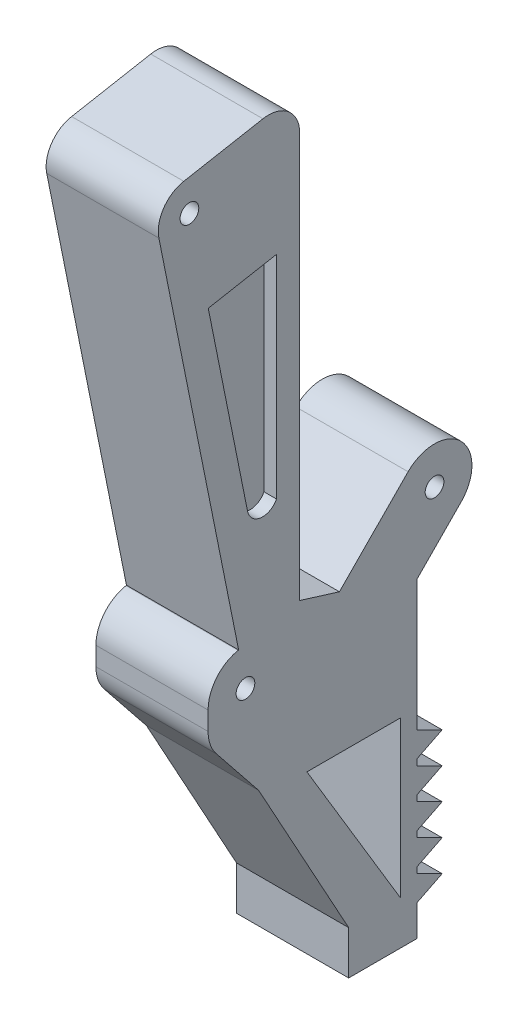
SolidWorks part; units mm, degrees
ref_plane "Front Plane" through (0, 0, 0) normal (0, 0, 1) x (1, 0, 0)
ref_plane "Top Plane" through (0, 0, 0) normal (0, 1, 0) x (1, 0, 0)
ref_plane "Right Plane" through (0, 0, 0) normal (1, 0, 0) x (0, 0, -1)
sketch "Sketch1" plane through (0, 0, 0) normal (1, 0, 0) x (0, 0, -1)
  line L0 (62.92, -2.8978) -> (49.1204, 65.7285)
  line L1 (49.1204, 65.7285) -> (72.7238, 70.0736)
  line L2 (72.7238, 70.0736) -> (72.7238, -0.9264)
  line L3 (72.7238, -0.9264) -> (62.92, -2.8978)
  line L4 (62.92, -2.8978) -> (58.0182, -3.8835)
  line L5 (58.0182, -3.8835) -> (58.0182, -13.8835)
  line L6 (58.0182, -13.8835) -> (66.1421, -24.0325)
  line L7 (66.1421, -24.0325) -> (80.5827, -50.3283)
  line L8 (80.5827, -50.3283) -> (80.5827, -57.3283)
  line L9 (80.5827, -57.3283) -> (91.5827, -57.3283)
  line L10 (91.5827, -57.3283) -> (91.5827, -7.3283)
  line L11 (72.7238, -0.9264) -> (79.0967, -2.898)
  line L12 (79.0967, -2.898) -> (90.1207, 8.2756)
  line L13 (91.5827, -7.3283) -> (98.6059, -0.2097)
  line L14 (98.6059, -0.2097) -> (90.1207, 8.2756) construction
  arc A0 (98.6059, -0.2097) -> (90.0639, 8.218) centre (94.3633, 4.0329) ccw
  dimension "D1" = 70
  dimension "D2" = 24
  dimension "D3" = 71
  dimension "D4" = 10
  dimension "D5" = 15
  dimension "D6" = 10
  dimension "D7" = 13
  dimension "D8" = 30
  dimension "D9" = 7
  dimension "D10" = 11
  dimension "D11" = 50
  dimension "D12" = 10
  dimension "D15" = 12
extrude "Boss-Extrude1" add sketch "Sketch1" along normal mid plane 18 contours L3 L2 L1 L0 | L13 L14 L12 L11 L3 L4 L5 L6 L7 L8 L9 L10 | L14 A0
sketch "Sketch2" plane through (9, 0, 0) normal (1, 0, 0) x (0, 0, -1)
  line L0 (88.8827, -50.3283) -> (88.8827, -25.3283)
  line L1 (88.8827, -25.3283) -> (73.8827, -25.3283)
  line L2 (73.8827, -25.3283) -> (88.8827, -50.3283)
  line L3 (91.5827, -57.3283) -> (91.5827, -7.3283) construction
  dimension "D1" = 15
  dimension "D2" = 25
  dimension "D3" = 0
  dimension "D4" = 2.7
extrude "Cut-Extrude1" cut sketch "Sketch2" against normal blind 25
sketch "Sketch3" plane through (9, 0, 0) normal (1, 0, 0) x (0, 0, -1)
  line L0 (91.5827, -52.3283) -> (95.5827, -50.3283)
  line L1 (91.5827, -57.3283) -> (91.5827, -7.3283) construction
  line L2 (95.5827, -50.3283) -> (91.5827, -48.3283)
  line L3 (91.5827, -50.3283) -> (95.5827, -50.3283)
  line L4 (80.5827, -57.3283) -> (91.5827, -57.3283) construction
  line M12 (91.5827, -57.3283) -> (91.5827, -7.3283)
  dimension "D1" = 5
  dimension "D2" = 4
  dimension "D3" = 2
  dimension "D4" = 4
extrude "Boss-Extrude2" add sketch "Sketch3" against normal blind 18 contours L3 L0 M12 | L3 L2 M12
pattern_linear "LPattern1" count 5 spacing 5 along (0, 1, 0) of "Boss-Extrude2"
fillet "Fillet1" radius 6 2 edges at (0, -13.8835, -58.0182) (0, -3.8835, -58.0182)
fillet "Fillet2" radius 5 2 edges at (0, 70.0736, -72.7238) (0, 65.7285, -49.1204)
sketch "Sketch4" plane through (9, 0, 0) normal (1, 0, 0) x (0, 0, -1)
  circle A0 centre (55.0243, 61.7313) radius 1.5
  dimension "D1" = 3
extrude "Cut-Extrude2" cut sketch "Sketch4" against normal blind 25
sketch "Sketch5" plane through (9, 0, 0) normal (1, 0, 0) x (0, 0, -1)
  circle A0 centre (94.3633, 4.0329) radius 1.5
  circle A1 centre (64.0182, -8.7971) radius 1.5
  dimension "D1" = 3
  dimension "D2" = 3
extrude "Cut-Extrude3" cut sketch "Sketch5" against normal blind 25
sketch "Sketch6" plane through (9, 0, 0) normal (1, 0, 0) x (0, 0, -1)
  line L0 (68.9902, 49.0502) -> (68.9902, 15.0502)
  line L1 (72.7238, 64.0691) -> (72.7238, -0.9264) construction
  line L2 (58.046, 47.0356) -> (64.3545, 15.6635)
  line L3 (62.92, -2.8978) -> (50.1224, 60.7456) construction
  line L4 (57.9365, 47.0154) -> (68.9902, 49.0502)
  line L5 (54.119, 66.6487) -> (66.8186, 68.9865) construction
  arc A0 (64.3545, 15.6635) -> (68.9902, 15.0502) centre (66.7773, 16.1507) ccw
  dimension "D4" = 2.4714
  dimension "D1" = 20
  dimension "D2" = 34
  dimension "D3" = 32
extrude "Cut-Extrude4" cut sketch "Sketch6" against normal blind 2 contours L2 A0 L0 L4
sketch "Sketch7" plane through (-9, 0, 0) normal (-1, 0, 0) x (0, 0, 1)
  line L0 (-68.3074, 48.9245) -> (-56.9345, 46.8309)
  line L1 (-56.9345, 46.8309) -> (-63.3692, 14.8309)
  line L2 (-68.3074, 48.9245) -> (-68.3074, 14.9245)
  line L3 (-72.7238, 64.0691) -> (-72.7238, -0.9264) construction
  line L4 (-62.92, -2.8978) -> (-50.1224, 60.7456) construction
  line L5 (-54.119, 66.6487) -> (-66.8186, 68.9865) construction
  arc A0 (-68.3074, 14.9245) -> (-63.3692, 14.8309) centre (-65.8374, 14.9245) ccw
  point P10 (-62.621, 47.8777)
  dimension "D4" = 2.47
  dimension "D1" = 20
  dimension "D2" = 34
  dimension "D3" = 32
extrude "Cut-Extrude5" cut sketch "Sketch7" against normal blind 2
